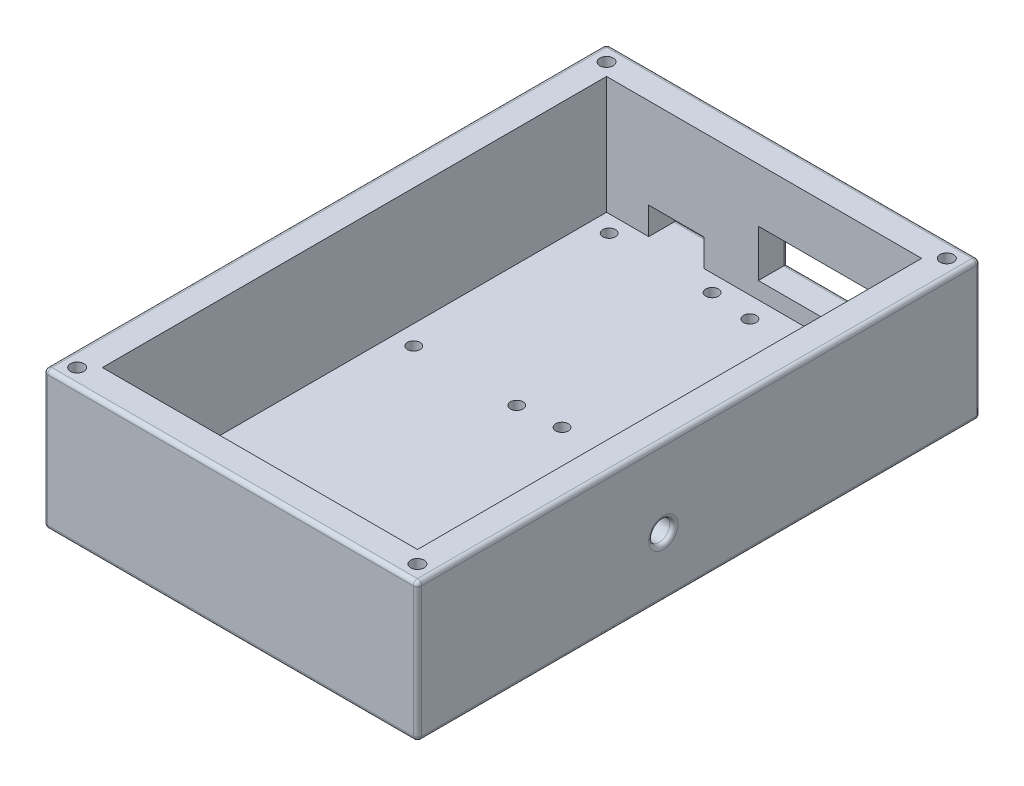
SolidWorks part; units mm, degrees
ref_plane "前基準面" through (0, 0, 0) normal (0, 0, 1) x (1, 0, 0)
ref_plane "上基準面" through (0, 0, 0) normal (0, 1, 0) x (1, 0, 0)
ref_plane "右基準面" through (0, 0, 0) normal (1, 0, 0) x (0, 0, -1)
sketch "草圖1" plane through (0, 0, 0) normal (0, 1, 0) x (1, 0, 0)
  line L1 (-44.5, 67) -> (44.5, 67)
  line L2 (-44.5, 67) -> (-44.5, -67)
  line L3 (-44.5, -67) -> (44.5, -67)
  line L4 (44.5, 67) -> (44.5, -67)
  line L5 (-44.5, 67) -> (44.5, -67) construction
  line L6 (-44.5, -67) -> (44.5, 67) construction
  point P0 (0, 0)
  dimension "D1" = 89
  dimension "D2" = 134
extrude "填料-伸長2" add sketch "草圖1" along normal mid plane 33
sketch "草圖4" plane through (0, 16.5, 0) normal (0, 1, 0) x (1, 0, 0)
  line L6 (-37.5, 60) -> (37.5, 60)
  line L7 (-37.5, 60) -> (-37.5, -60)
  line L8 (-37.5, -60) -> (37.5, -60)
  line L9 (37.5, 60) -> (37.5, -60)
  line L10 (-37.5, 60) -> (37.5, -60) construction
  line L11 (-37.5, -60) -> (37.5, 60) construction
  point P0 (0, 0)
  dimension "D2" = 75
  dimension "D1" = 120
extrude "除料-伸長1" cut sketch "草圖4" against normal blind 28
sketch "Sketch4" plane through (0, -16.5, 0) normal (0, -1, 0) x (1, 0, 0)
  circle A0 centre (-32.8808, -9.5) radius 1.5
  circle A1 centre (-8.3808, -9.5) radius 1.5
  circle A2 centre (-32.8808, -56) radius 1.5
  circle A3 centre (-8.3808, -56) radius 1.5
  circle A4 centre (1.5402, -10.375) radius 1.5
  circle A5 centre (32.579, -10.375) radius 1.5
  circle A6 centre (1.5402, -55.079) radius 1.5
  circle A7 centre (32.579, -55.079) radius 1.5
extrude "Cut-Extrude1" cut sketch "Sketch4" against normal up to next
sketch "Sketch7" plane through (0, 0, -67) normal (0, 0, -1) x (-1, 0, 0)
  line L0 (21.2605, -8.65) -> (20.4405, -8.65) construction
  line L5 (14.2455, -5) -> (14.2455, -11.5)
  line L6 (14.2455, -5) -> (27.4555, -5)
  line L8 (-44.5, 16.5) -> (-44.5, -16.5) construction
  line L9 (14.2455, -11.5) -> (27.4555, -11.5)
  line L10 (27.4555, -5) -> (27.4555, -11.5)
  line L11 (14.2455, -5) -> (27.4555, -11.5) construction
  line L12 (14.2455, -11.5) -> (27.4555, -5) construction
  line L13 (37.5, -11.5) -> (37.5, 16.5) construction
  line L14 (-44.5, -16.5) -> (44.5, -16.5) construction
  line L15 (-35.5596, 3.7004) -> (-35.5596, -7.5)
  line L16 (-35.5596, 3.7004) -> (1.3666, 3.7004)
  line L17 (-35.5596, -7.5) -> (1.3666, -7.5)
  line L18 (1.3666, 3.7004) -> (1.3666, -7.5)
  line L19 (-35.5596, 3.7004) -> (1.3666, -7.5) construction
  line L20 (-35.5596, -7.5) -> (1.3666, 3.7004) construction
  point P0 (20.8505, -8.65)
  point P2 (20.8505, -8.25)
  point P14 (-17.0965, -1.8998)
  point P15 (-37.5227, -1.7433)
  dimension "D1" = 6.5
  dimension "D2" = 13.21
  dimension "D3" = 10.0445
  dimension "D4" = 5
  dimension "D5" = 8.9404
  dimension "D6" = 11.2004
  dimension "D8" = 9
extrude "Cut-Extrude2" cut sketch "Sketch7" against normal up to next
sketch "Sketch8" plane through (44.5, 0, 0) normal (1, 0, 0) x (0, 0, -1)
  line L0 (-8.471, -0.95) -> (-8.471, 16.5) construction
  line L1 (-8.471, -2.1) -> (-8.471, 0.2) construction
  line L2 (-67, 16.5) -> (67, 16.5) construction
  line L3 (-8.471, 16.5) -> (-8.471, -11.5) construction
  line L4 (-60, -11.5) -> (60, -11.5) construction
  line L5 (0.634, -2.3) -> (-45.466, -2.3) construction
  circle A0 centre (-8.471, -2.3) radius 2.5
  dimension "D1" = 5
extrude "Cut-Extrude3" cut sketch "Sketch8" against normal up to next
fillet "Fillet3" radius 1 21 edges at (44.5, 16.5, 0) (44.5, -16.5, 0) (44.5, -2.3, 5.971) (0, 16.5, 67) (44.5, 0, 67) (0, -16.5, 67) (-44.5, 16.5, 0) (-44.5, 0, 67) (-44.5, -16.5, 0) (44.5, 0, -67) (0, 16.5, -67) (-44.5, 0, -67) (0, -16.5, -67) (-1.3666, -1.8998, -67) (17.0965, 3.7004, -67) (35.5596, -1.8998, -67) (17.0965, -7.5, -67) (-27.4555, -8.25, -67) (-20.8505, -5, -67) (-14.2455, -8.25, -67) (-20.8505, -11.5, -67)
sketch "Sketch9" plane through (0, 16.5, 0) normal (0, 1, 0) x (1, 0, 0)
  circle A0 centre (-40.4948, 62.9948) radius 1.6
  circle A1 centre (40.4948, 62.9948) radius 1.6
  circle A2 centre (40.4948, -62.9948) radius 1.6
  circle A3 centre (-40.4948, -62.9948) radius 1.6
  dimension "D1" = 3.2
  dimension "D2" = 3.2
  dimension "D3" = 3.2
  dimension "D4" = 3.2
extrude "Cut-Extrude4" cut sketch "Sketch9" against normal through all
sketch "Sketch10" plane through (0, -16.5, 0) normal (0, -1, 0) x (1, 0, 0)
  line L1 (-40.4948, 66.1702) -> (-43.2448, 64.5825)
  line L2 (-43.2448, 64.5825) -> (-43.2448, 61.4071)
  line L3 (-43.2448, 61.4071) -> (-40.4948, 59.8194)
  line L4 (-40.4948, 59.8194) -> (-37.7448, 61.4071)
  line L5 (-37.7448, 61.4071) -> (-37.7448, 64.5825)
  line L6 (-37.7448, 64.5825) -> (-40.4948, 66.1702)
  line L7 (0, 0) -> (-43.5, 0) construction
  line L8 (-43.5, 66) -> (-43.5, -66) construction
  line L9 (-43.5, 0) -> (44.5, 0) construction
  line L10 (44.5, -67) -> (44.5, 67) construction
  line L11 (0, 0) -> (0, 67) construction
  line L12 (-44.5, 67) -> (44.5, 67) construction
  line L13 (0, 0) -> (0, -67) construction
  line L14 (-44.5, -67) -> (44.5, -67) construction
  line L15 (37.7448, 64.5825) -> (40.4948, 66.1702)
  line L16 (37.7448, 61.4071) -> (37.7448, 64.5825)
  line L17 (40.4948, 59.8194) -> (37.7448, 61.4071)
  line L18 (43.2448, 61.4071) -> (40.4948, 59.8194)
  line L19 (43.2448, 64.5825) -> (43.2448, 61.4071)
  line L20 (40.4948, 66.1702) -> (43.2448, 64.5825)
  line L21 (37.7448, -61.4071) -> (37.7448, -64.5825)
  line L22 (40.4948, -59.8194) -> (37.7448, -61.4071)
  line L23 (43.2448, -61.4071) -> (40.4948, -59.8194)
  line L24 (43.2448, -64.5825) -> (43.2448, -61.4071)
  line L25 (40.4948, -66.1702) -> (43.2448, -64.5825)
  line L26 (37.7448, -64.5825) -> (40.4948, -66.1702)
  line L27 (-37.7448, -64.5825) -> (-40.4948, -66.1702)
  line L28 (-37.7448, -61.4071) -> (-37.7448, -64.5825)
  line L29 (-40.4948, -59.8194) -> (-37.7448, -61.4071)
  line L30 (-43.2448, -61.4071) -> (-40.4948, -59.8194)
  line L31 (-43.2448, -64.5825) -> (-43.2448, -61.4071)
  line L32 (-40.4948, -66.1702) -> (-43.2448, -64.5825)
  circle A1 centre (-40.4948, 62.9948) radius 2.75 construction
  dimension "D1" = 5.5
extrude "Cut-Extrude5" cut sketch "Sketch10" against normal blind 2.5
